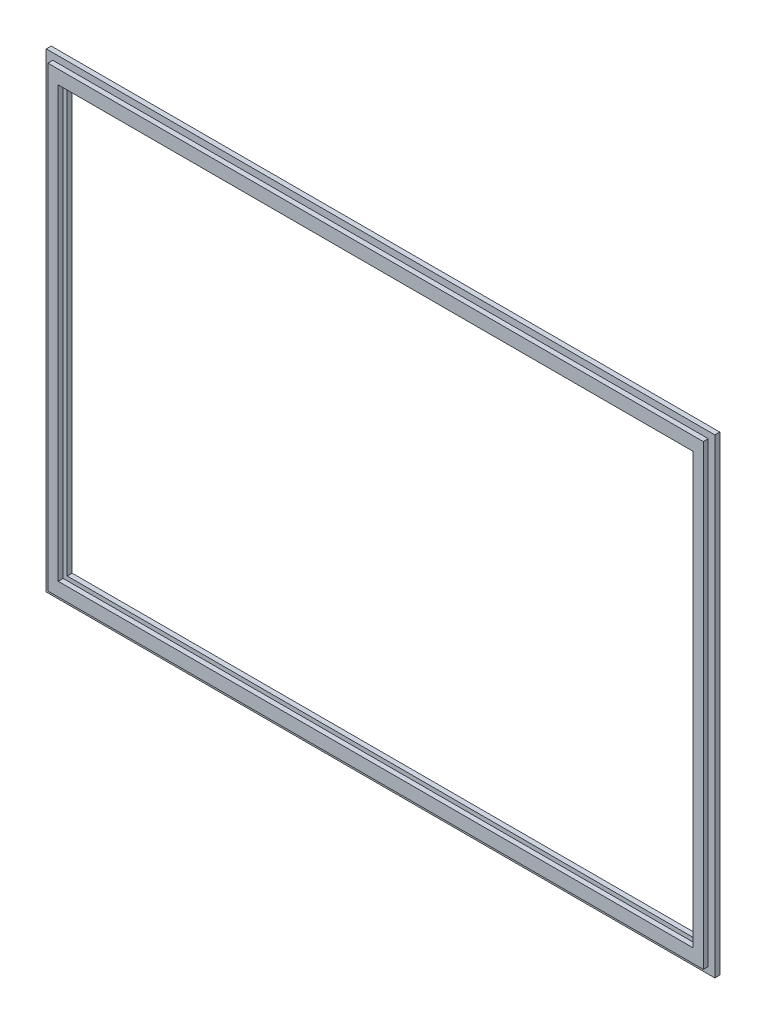
SolidWorks part; units mm, degrees
ref_plane "Front Plane" through (0, 0, 0) normal (0, 0, 1) x (1, 0, 0)
ref_plane "Top Plane" through (0, 0, 0) normal (0, 1, 0) x (1, 0, 0)
ref_plane "Right Plane" through (0, 0, 0) normal (1, 0, 0) x (0, 0, -1)
sketch "Sketch1" plane through (0, 0, 0) normal (0, 0, 1) x (1, 0, 0)
  line L1 (38.5, -26.075) -> (-38.5, -26.075)
  line L2 (38.5, -26.075) -> (38.5, 26.075)
  line L3 (38.5, 26.075) -> (-38.5, 26.075)
  line L4 (-38.5, -26.075) -> (-38.5, 26.075)
  line L5 (38.5, -26.075) -> (-38.5, 26.075) construction
  line L6 (38.5, 26.075) -> (-38.5, -26.075) construction
  line L7 (39.75, -27.725) -> (-39.75, -27.725)
  line L8 (39.75, -27.725) -> (39.75, 27.725)
  line L9 (39.75, 27.725) -> (-39.75, 27.725)
  line L10 (-39.75, -27.725) -> (-39.75, 27.725)
  line L11 (39.75, -27.725) -> (-39.75, 27.725) construction
  line L12 (39.75, 27.725) -> (-39.75, -27.725) construction
  point P0 (0, 0)
  point P6 (0, 0)
  dimension "D1" = 77
  dimension "D2" = 79.5
  dimension "D3" = 52.15
  dimension "D4" = 55.45
extrude "Boss-Extrude1" add sketch "Sketch1" along normal blind 0.6
sketch "Sketch2" plane through (0, 0, 0) normal (0, 0, -1) x (-1, 0, 0)
  line L8 (38, -25.575) -> (38, 25.575)
  line L9 (-38, -25.575) -> (38, -25.575)
  line L10 (-38, 25.575) -> (-38, -25.575)
  line L11 (38, 25.575) -> (-38, 25.575)
  line L12 (38, -25.575) -> (38, 25.575)
  line L13 (-38, -25.575) -> (38, -25.575)
  line L14 (-38, 25.575) -> (-38, -25.575)
  line L15 (38, 25.575) -> (-38, 25.575)
  line L20 (-40.55, -28.525) -> (40.55, -28.525)
  line L21 (40.55, -28.525) -> (40.55, 28.525)
  line L22 (-40.55, 28.525) -> (-40.55, -28.525)
  line L23 (40.55, 28.525) -> (-40.55, 28.525)
  line L24 (-40.55, -28.525) -> (40.55, -28.525)
  line L25 (40.55, -28.525) -> (40.55, 28.525)
  line L26 (-40.55, 28.525) -> (-40.55, -28.525)
  line L27 (40.55, 28.525) -> (-40.55, 28.525)
  dimension "D1" = 0.5
  dimension "D2" = 0.8
extrude "Boss-Extrude2" add sketch "Sketch2" along normal blind 0.6
